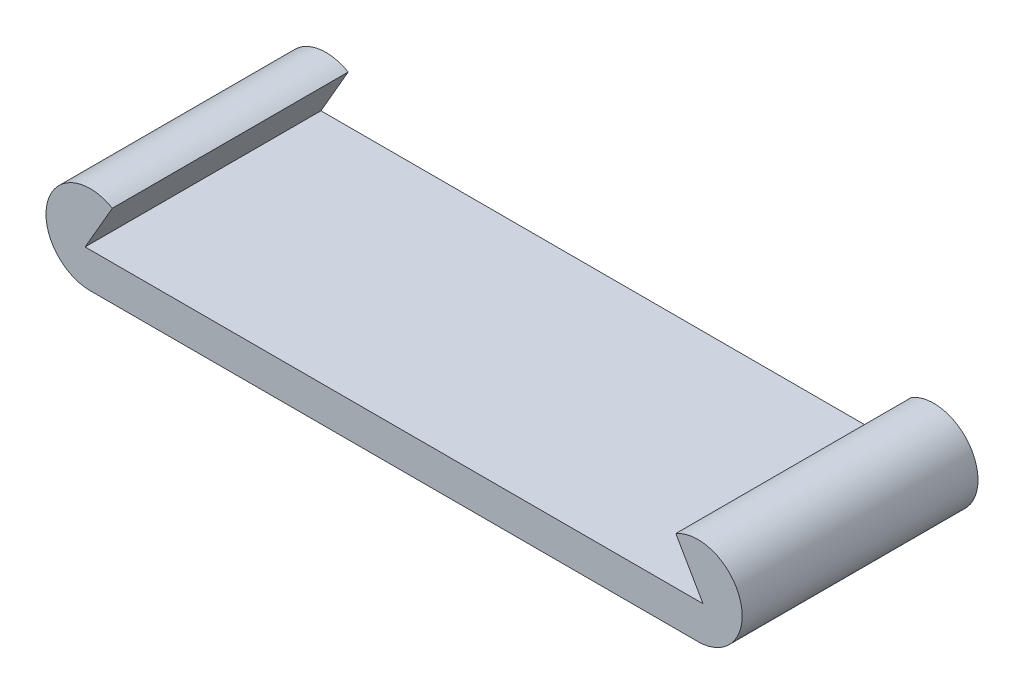
SolidWorks part; units mm, degrees
ref_plane "Front Plane" through (0, 0, 0) normal (0, 0, 1) x (1, 0, 0)
ref_plane "Top Plane" through (0, 0, 0) normal (0, 1, 0) x (1, 0, 0)
ref_plane "Right Plane" through (0, 0, 0) normal (1, 0, 0) x (0, 0, -1)
sketch "Sketch1" plane through (0, 0, 0) normal (0, 0, 1) x (1, 0, 0)
  line L0 (0, 0) -> (0, 30.5521) construction
  line L1 (13.1, 1.5) -> (11.9453, 3.5)
  line L2 (-13.1, 1.5) -> (-11.9453, 3.5)
  line L3 (13.1, 1.5) -> (-13.1, 1.5)
  line L5 (-12.8831, 0) -> (12.8831, 0)
  arc A0 (11.9453, 3.5) -> (12.8831, 0) centre (12.8831, 1.8756) cw
  arc A1 (-11.9453, 3.5) -> (-12.8831, 0) centre (-12.8831, 1.8756) ccw
  dimension "D1" = 60
  dimension "D2" = 2
  dimension "D3" = 1.5
  dimension "D4" = 26.2
extrude "Boss-Extrude1" add sketch "Sketch1" along normal blind 10
